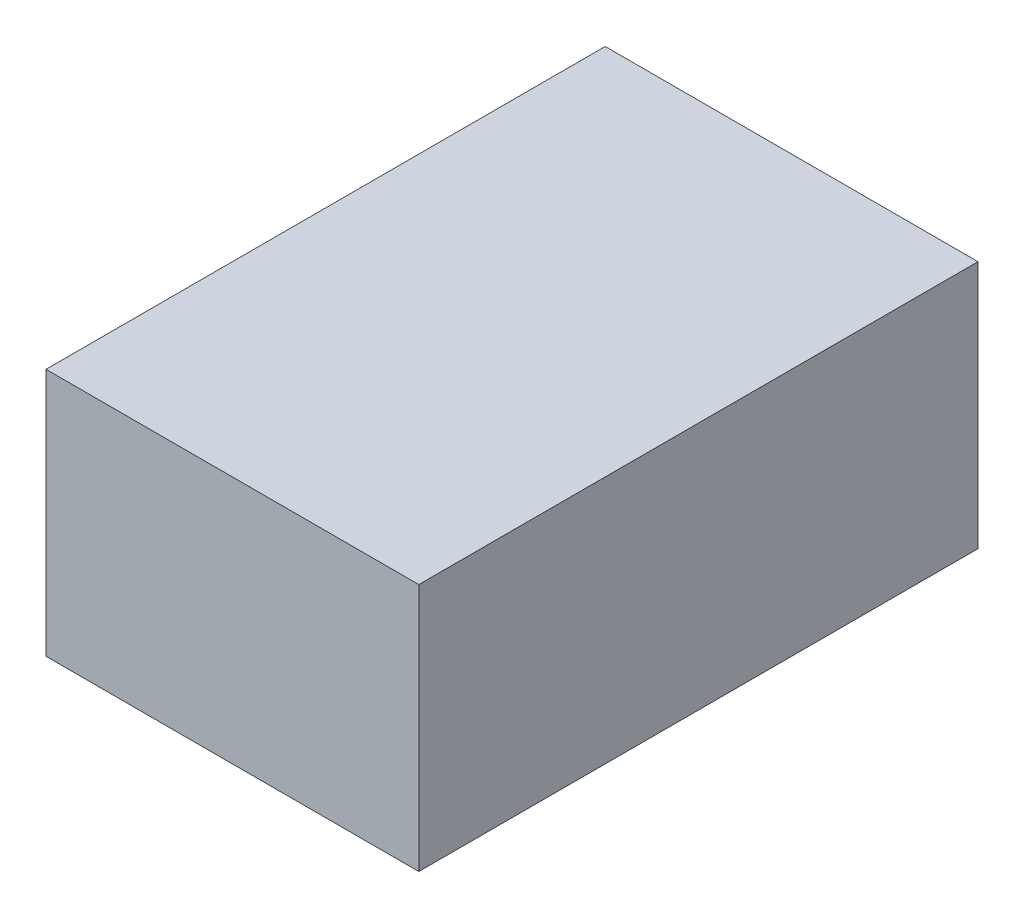
SolidWorks part; units mm, degrees
ref_plane "Front Plane" through (0, 0, 0) normal (0, 0, 1) x (1, 0, 0)
ref_plane "Top Plane" through (0, 0, 0) normal (0, 1, 0) x (1, 0, 0)
ref_plane "Right Plane" through (0, 0, 0) normal (1, 0, 0) x (0, 0, -1)
sketch "Sketch1" plane through (0, 0, 0) normal (0, 0, 1) x (1, 0, 0)
  line L0 (0, 35.8977) -> (0, -14.9023)
  line L1 (0, 35.8977) -> (76.2, 35.8977)
  line L6 (76.2, 35.8977) -> (76.2, -14.9023)
  line L7 (76.2, -14.9023) -> (0, -14.9023)
  dimension "D1" = 50.8
  dimension "D2" = 50.8
  dimension "D4" = 76.2
extrude "Boss-Extrude1" add sketch "Sketch1" along normal blind 114.3
sketch "Sketch2" plane through (0, 0, 0) normal (0, 1, 0) x (1, 0, 0)
  line L0 (0, -114.3) -> (76.2, -114.3) construction
  line L1 (1.778, -112.522) -> (74.422, -112.522)
  line L2 (1.778, -112.522) -> (1.778, -1.778)
  line L3 (1.778, -1.778) -> (74.422, -1.778)
  line L4 (74.422, -112.522) -> (74.422, -1.778)
  line L5 (0, -114.3) -> (0, 0) construction
  line L6 (76.2, -114.3) -> (76.2, 0) construction
  line L7 (0, 0) -> (76.2, 0) construction
  dimension "D1" = 1.778
  dimension "D2" = 1.778
  dimension "D3" = 1.778
  dimension "D4" = 1.778
sketch "Sketch3" plane through (0, -14.9023, 0) normal (0, -1, 0) x (1, 0, 0)
  line L0 (0, 0) -> (76.2, 0) construction
  line L2 (1.778, 112.522) -> (74.422, 112.522)
  line L3 (1.778, 112.522) -> (1.778, 1.778)
  line L4 (0, 114.3) -> (76.2, 114.3) construction
  line L5 (0, 114.3) -> (0, 0) construction
  line L6 (1.778, 103.632) -> (10.668, 103.632)
  line L7 (10.668, 112.522) -> (10.668, 103.632)
  line L8 (1.778, 1.778) -> (74.422, 1.778)
  line L9 (74.422, 103.632) -> (65.532, 103.632)
  line L10 (65.532, 112.522) -> (65.532, 103.632)
  line L11 (76.2, 114.3) -> (76.2, 0) construction
  line L12 (65.532, 10.668) -> (65.532, 1.778)
  line L13 (74.422, 10.668) -> (65.532, 10.668)
  line L14 (74.422, 112.522) -> (74.422, 1.778)
  line L17 (10.668, 10.668) -> (1.778, 10.668)
  line L18 (10.668, 10.668) -> (10.668, 1.778)
  circle A0 centre (6.35, 107.95) radius 2.286
  circle A1 centre (69.85, 107.95) radius 2.286
  circle A4 centre (69.85, 6.35) radius 2.286
  circle A5 centre (6.35, 6.35) radius 2.286
  dimension "D3" = 6.35
  dimension "D5" = 6.35
  dimension "D1" = 8.89
  dimension "D2" = 8.89
  dimension "D4" = 6.35
  dimension "D8" = 6.35
  dimension "D9" = 6.35
  dimension "D10" = 6.35
  dimension "D11" = 6.35
  dimension "D12" = 6.35
  dimension "D13" = 8.89
  dimension "D14" = 8.89
  dimension "D15" = 8.89
  dimension "D16" = 8.89
extrude "Cut-Extrude2" cut sketch "Sketch3" against normal blind 49.022 contours L17 L18 L8 L12 L13 L14 L9 L10 L2 L7 L6 L3
sketch "Sketch6" plane through (0, -14.9023, 0) normal (0, -1, 0) x (-1, 0, 0)
  line L0 (-6.35, -6.35) -> (-69.85, -6.35) construction
  line L1 (-69.85, -107.95) -> (-6.35, -107.95) construction
  line L2 (-6.35, -107.95) -> (-6.35, -6.35) construction
  line L3 (-69.85, -6.35) -> (-69.85, -107.95) construction
  line L4 (-76.2, -114.3) -> (-76.2, 0) construction
  line L5 (0, -114.3) -> (0, 0) construction
  line L6 (0, 0) -> (-76.2, 0) construction
  line L7 (0, -114.3) -> (-76.2, -114.3) construction
  circle A0 centre (-69.85, -6.35) radius 2.286
  circle A1 centre (-6.35, -6.35) radius 2.286
  circle A2 centre (-6.35, -107.95) radius 2.286
  circle A3 centre (-69.85, -107.95) radius 2.286
  dimension "D1" = 4.572
  dimension "D2" = 6.35
  dimension "D3" = 6.35
  dimension "D4" = 6.35
  dimension "D5" = 6.35
extrude "Cut-Extrude3" cut sketch "Sketch6" against normal blind 5.08 draft 3
sketch "Sketch10" plane through (0, 0, 0) normal (0, 0, -1) x (-1, 0, 0)
  line L0 (-76.2, 35.8977) -> (0, 35.8977) construction
  line L1 (-63.5, 33.3577) -> (-48.26, 33.3577)
  line L2 (-63.5, 33.3577) -> (-63.5, 18.1177)
  line L3 (-63.5, 18.1177) -> (-48.26, 18.1177)
  line L4 (-48.26, 33.3577) -> (-48.26, 18.1177)
  line L5 (-28.26, 33.3577) -> (-11.242, 33.3577)
  line L6 (-28.26, 33.3577) -> (-28.26, 18.1177)
  line L7 (-28.26, 18.1177) -> (-11.242, 18.1177)
  line L8 (-11.242, 33.3577) -> (-11.242, 18.1177)
  line L9 (-76.2, -14.9023) -> (-76.2, 35.8977) construction
  point P10 (-55.88, 33.3577)
  dimension "D1" = 2.54
  dimension "D2" = 2.54
  dimension "D3" = 12.7
  dimension "D4" = 15.24
  dimension "D5" = 15.24
  dimension "D6" = 20
  dimension "D7" = 15.24
  dimension "D8" = 17.018
extrude "Cut-Extrude4" cut sketch "Sketch10" against normal blind 5.08
